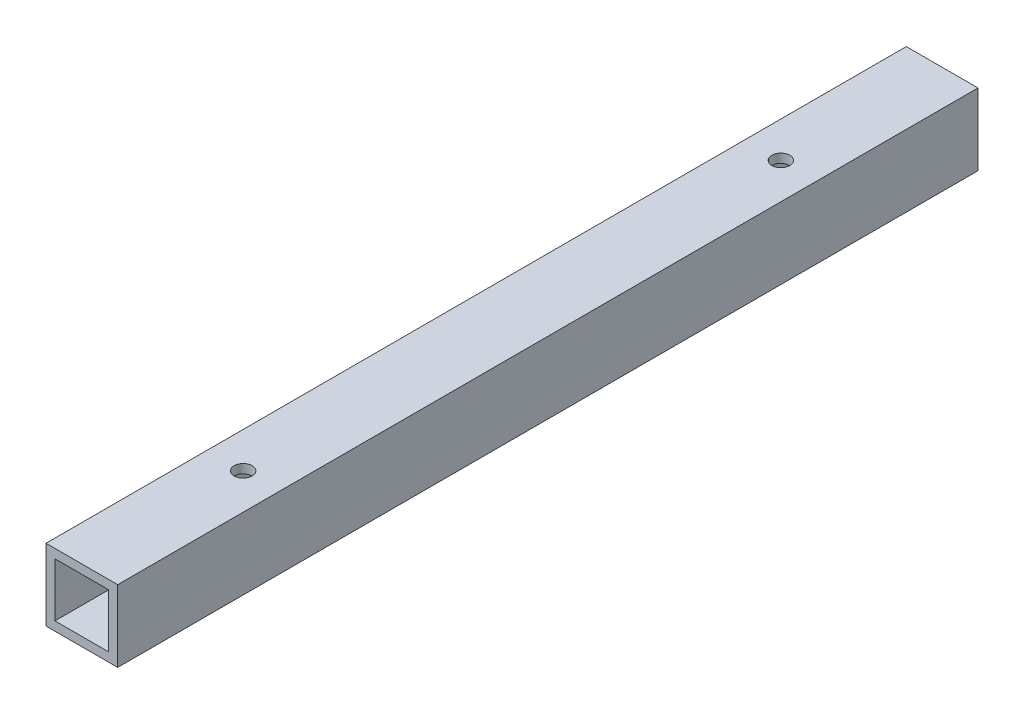
SolidWorks part; units mm, degrees
material "6061 Alloy"
ref_plane "Front Plane" through (0, 0, 0) normal (0, 0, 1) x (1, 0, 0)
ref_plane "Top Plane" through (0, 0, 0) normal (0, 1, 0) x (1, 0, 0)
ref_plane "Right Plane" through (0, 0, 0) normal (1, 0, 0) x (0, 0, -1)
sketch "Sketch1" plane through (0, 0, 0) normal (0, 0, 1) x (1, 0, 0)
  line L0 (12.7, 0) -> (9.525, 0) construction
  line L1 (-12.7, 0) -> (12.7, 0) construction
  line L2 (0, 12.7) -> (0, -12.7)
  point P7 (0, 0)
sketch "Sketch2" plane through (0, 0, 0) normal (1, 0, 0) x (0, 0, -1)
  line L0 (152.4, 0) -> (-152.4, 0)
  point P4 (0, 0)
  dimension "Length" = 304.8
sketch "Sketch3" plane through (0, 0, 0) normal (0, 0, 1) x (1, 0, 0)
  line L0 (-12.7, 0) -> (12.7, 0) construction
  line L5 (12.7, -12.7) -> (-12.7, -12.7)
  line L6 (12.7, -12.7) -> (12.7, 12.7)
  line L11 (12.7, 12.7) -> (-12.7, 12.7)
  line L12 (-12.7, -12.7) -> (-12.7, 12.7)
  line L14 (12.7, -12.7) -> (-12.7, 12.7) construction
  line L15 (12.7, 12.7) -> (-12.7, -12.7) construction
  line L16 (9.525, -9.525) -> (-9.525, -9.525)
  line L17 (9.525, -9.525) -> (9.525, 9.525)
  line L18 (9.525, 9.525) -> (-9.525, 9.525)
  line L19 (-9.525, -9.525) -> (-9.525, 9.525)
  line L20 (9.525, -9.525) -> (-9.525, 9.525) construction
  line L21 (9.525, 9.525) -> (-9.525, -9.525) construction
  point P0 (0, 0)
  point P5 (0, 0)
  point P13 (9.525, -12.7)
  dimension "D1" = 3.175
  dimension "D3" = 25.4
  dimension "D4" = 25.4
extrude "Boss-Extrude1" add sketch "Sketch3" along normal up to vertex (152.4 mm away) and the other way up to vertex (152.4 mm away) up to point (0, 0, 152.4) other way up to point (0, 0, -152.4)
sketch "Sketch5" plane through (0, 0, 0) normal (1, 0, 0) x (0, 0, -1)
  line L0 (-152.4, 0) -> (152.4, 0) construction
  line L3 (-152.4, -12.7) -> (-152.4, 12.7) construction
  line L4 (152.4, -12.7) -> (152.4, 12.7) construction
  point P6 (-123.825, 0)
  point P7 (-114.3, 0)
  point P8 (114.3, 0)
  point P10 (123.825, 0)
  dimension "D1" = 28.575
  dimension "D2" = 38.1
  dimension "D3" = 28.575
  dimension "D4" = 38.1
sketch "Sketch6" plane through (0, 12.7, 0) normal (0, 1, 0) x (1, 0, 0)
  line L0 (0, 152.4) -> (0, -152.4) construction
  line L1 (12.7, 152.4) -> (-12.7, 152.4) construction
  line L2 (12.7, -152.4) -> (-12.7, -152.4) construction
  line L3 (-12.7, 0) -> (12.7, 0) construction
  line L4 (-12.7, -152.4) -> (-12.7, 152.4) construction
  line L5 (12.7, -152.4) -> (12.7, 152.4) construction
  circle A0 centre (0, -95.25) radius 3.175
  circle A1 centre (0, 95.25) radius 3.175
  point P16 (0, 0)
  dimension "D1" = 6.35
  dimension "D2" = 57.15
extrude "Cut-Extrude1" cut sketch "Sketch6" against normal through all
equation "\"D1@Sketch3\"=\"Wall thickness@Sketch1\""
equation "\"D1@Sketch5\"=\"Width@Sketch1\"*1.125"
equation "\"D2@Sketch5\"=\"Width@Sketch1\"*1.5"
equation "\"D3@Sketch5\"=\"D1@Sketch5\""
equation "\"D4@Sketch5\"=\"D2@Sketch5\""
equation "\"D2@Sketch3\"=\"Wall Thickness@Sketch1\""
